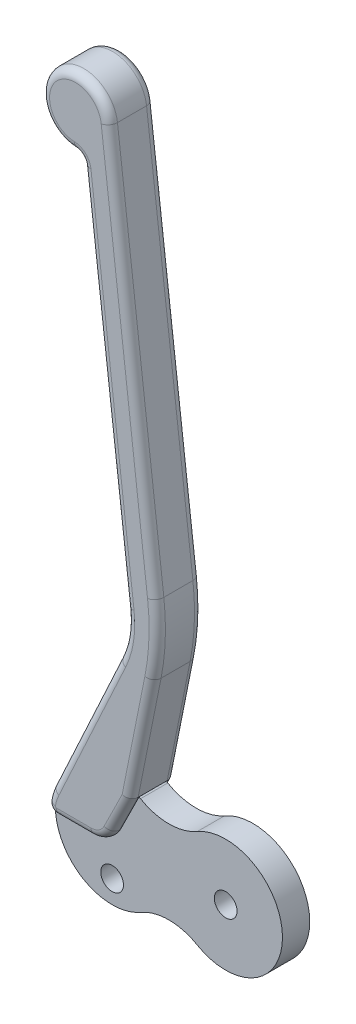
SolidWorks part; units mm, degrees
material "A356-T6 cast aluminum alloy"
ref_plane "Front Plane" through (0, 0, 0) normal (1, 0, 0) x (0, 1, 0)
ref_plane "Top Plane" through (0, 0, 0) normal (0, 0, 1) x (0, 1, 0)
ref_plane "Right Plane" through (0, 0, 0) normal (0, 1, 0) x (-1, 0, 0)
sketch "Sketch1" plane through (0, 0, 0) normal (0, 0, 1) x (0, 1, 0)
  line L0 (0, 31.5567) -> (0, -42.8575) construction
  line L1 (-28.6344, 0) -> (26.3766, 0) construction
  arc A0 (-10.8253, 6.25) -> (10.8253, 6.25) centre (0, 0) ccw
  circle A1 centre (0, 0) radius 2.5
  arc A2 (10.8253, 18.75) -> (-10.8253, 18.75) centre (0, 25) ccw
  circle A3 centre (-7.5, 25) radius 2.5
  arc A4 (-10.8253, 18.75) -> (-10.8253, 6.25) centre (-21.6506, 12.5) cw
  arc A5 (10.8253, 18.75) -> (10.8253, 6.25) centre (21.6506, 12.5) ccw
  point P12 (0, -12.5)
  point P13 (0, 37.5)
  dimension "D1" = 25
  dimension "D2" = 5
  dimension "D3" = 25
  dimension "D5" = 12.5
  dimension "D6" = 5
  dimension "D4" = 50
  dimension "D7" = 7.5
extrude "Boss-Extrude1" add sketch "Sketch1" along normal mid plane 6
sketch "Sketch2" plane through (0, 0, 0) normal (0, 0, 1) x (0, 1, 0)
  line L0 (0, 35.3078) -> (0, 27.6366)
  line L1 (62.5, 88.0868) -> (62.5, -25.8793) construction
  line L2 (136.51, 31.0677) -> (144.01, 31.0677) construction
  line L3 (51.9925, 13.4149) -> (137.3999, 23.6206)
  line L4 (5.2463, 36.3458) -> (36.996, 21.6648)
  line L5 (47.763, 19.9593) -> (127.2548, 29.4582)
  line L6 (-7.5, 25) -> (-12.5, 25) construction
  line L7 (-18.0582, 12.5) -> (119.8577, 12.5) construction
  line L8 (36.2627, 14.031) -> (11.0196, 19.075)
  line L9 (2.7806, 23.1561) -> (11.0196, 19.075)
  line L10 (46.06, 63.0617) -> (46.06, -8.1148) construction
  line L11 (-13.49, 46.0258) -> (-13.49, 15.6249) construction
  arc A0 (127.2548, 29.4582) -> (129.0159, 31.3648) centre (127.0175, 31.444) ccw
  arc A1 (137.3999, 23.6206) -> (129.0159, 31.3648) centre (136.51, 31.0677) ccw
  arc A2 (10.8253, 18.75) -> (-10.8253, 18.75) centre (0, 25) ccw construction
  arc A3 (36.996, 21.6648) -> (47.763, 19.9593) centre (45.39, 39.818) ccw
  circle A4 centre (-7.5, 25) radius 2.5 construction
  circle A5 centre (-7.5, 25) radius 2.5
  arc A6 (0, 27.6366) -> (2.7806, 23.1561) centre (5, 27.6366) ccw
  arc A7 (36.2627, 14.031) -> (51.9925, 13.4149) centre (46.06, 63.0617) ccw
  arc A9 (-10.8253, 6.25) -> (-10.8253, 18.75) centre (-21.6506, 12.5) ccw construction
  arc A10 (-10.8253, 6.25) -> (-10.8253, 18.75) centre (-21.6506, 12.5) ccw
  arc A11 (5.2463, 36.3458) -> (2.381, 37.2711) centre (0, 25) ccw
  arc A12 (-12.5, 25) -> (-10.8253, 18.75) centre (0, 25) ccw
  arc A13 (0, 35.3078) -> (2.381, 37.2711) centre (2, 35.3078) cw
  arc A15 (10.8253, 18.75) -> (10.8253, 6.25) centre (21.6506, 12.5) ccw construction
  point P39 (0.7517, 25)
  point P48 (44.1032, 13.1)
  dimension "D2" = 15
  dimension "D5" = 20
  dimension "D6" = 2
  dimension "D9" = 5
  dimension "D10" = 50
  dimension "D13" = 2
  dimension "D1" = 7
  dimension "D3" = 156.51
  dimension "D4" = 148.37
  dimension "D7" = 12.5
  dimension "D8" = 81.51
  dimension "D11" = 17.11
  dimension "D12" = 11.3
  dimension "D14" = 16.44
  dimension "D15" = 1.2
extrude "Boss-Extrude2" add sketch "Sketch2" along normal mid plane 10 contours A13 L0 A6 L9 L8 A7 L3 A1 A0 L5 A3 L4 A11
fillet "Fillet1" radius 1.8 26 edges at (-16.553, 23.6411, -5) (-13.1, 44.1032, -5) (-21.1156, 6.9001, -5) (-25, 0.7517, -5) (-31.4722, 0, -5) (-36.8508, 0.7276, -5) (-36.8951, 3.8416, -5) (-29.0053, 21.1211, -5) (-20.0643, 42.2611, -5) (-24.7087, 87.5089, -5) (-30.087, 128.4866, -5) (-36.577, 141.5989, -5) (-16.553, 23.6411, 5) (-13.1, 44.1032, 5) (-21.1156, 6.9001, 5) (-25, 0.7517, 5) (-31.4722, 0, 5) (-36.8508, 0.7276, 5) (-36.8951, 3.8416, 5) (-29.0053, 21.1211, 5) (-20.0643, 42.2611, 5) (-24.7087, 87.5089, 5) (-30.087, 128.4866, 5) (-36.577, 141.5989, 5) (-18.5178, 94.6962, -5) (-18.5178, 94.6962, 5)
